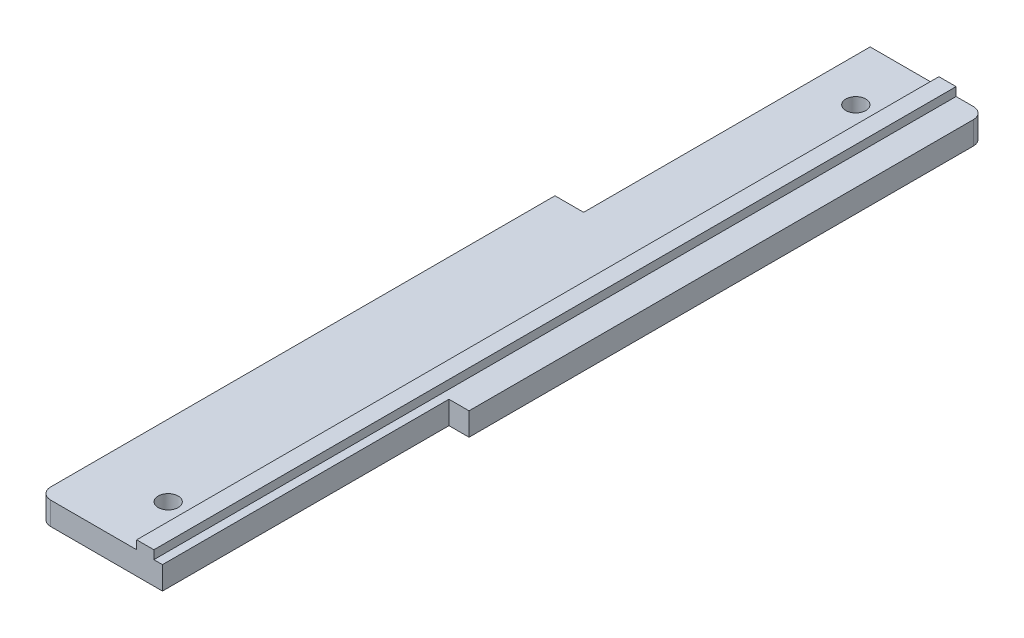
SolidWorks part; units mm, degrees
ref_plane "前视基准面" through (0, 0, 0) normal (0, 0, 1) x (1, 0, 0)
ref_plane "上视基准面" through (0, 0, 0) normal (0, 1, 0) x (1, 0, 0)
ref_plane "右视基准面" through (0, 0, 0) normal (1, 0, 0) x (0, 0, -1)
sketch "草图1" plane through (0, 0, 0) normal (0, 1, 0) x (1, 0, 0)
  line L1 (-12.5, -70) -> (12.5, -70)
  line L2 (-12.5, -70) -> (-12.5, 70)
  line L3 (-12.5, 70) -> (12.5, 70)
  line L4 (12.5, -70) -> (12.5, 70)
  line L5 (-12.5, -70) -> (12.5, 70) construction
  line L6 (-12.5, 70) -> (12.5, -70) construction
  point P0 (0, 0)
  dimension "D1" = 25
  dimension "D2" = 140
extrude "凸台-拉伸1" add sketch "草图1" along normal blind 4
sketch "草图2" plane through (0, 4, 0) normal (0, 1, 0) x (1, 0, 0)
  line L0 (0, 70) -> (0, -70) construction
  line L1 (12.5, 70) -> (-12.5, 70) construction
  line L2 (-12.5, -70) -> (12.5, -70) construction
  line L3 (0, 0) -> (12.5, 0) construction
  line L4 (12.5, -70) -> (12.5, 70) construction
  circle A0 centre (0, 0) radius 1.6 construction
  circle A1 centre (0, 20) radius 1.6 construction
  circle A2 centre (0, 40) radius 1.6 construction
  circle A3 centre (0, -40) radius 1.6 construction
  circle A4 centre (0, -20) radius 1.6 construction
  circle A5 centre (0, 10) radius 1.6
  circle A6 centre (0, 30) radius 1.6
  circle A7 centre (0, 50) radius 1.6
  circle A8 centre (0, -10) radius 1.6
  circle A9 centre (0, -30) radius 1.6
  circle A10 centre (0, -50) radius 1.6
  dimension "D1" = 3.2
  dimension "D4" = 3.2
  dimension "D3" = 20
  dimension "D5" = 10
  dimension "D7" = 20
  dimension "D2" = 3
  dimension "D6" = 3
sketch "草图3" plane through (0, 4, 0) normal (0, 1, 0) x (1, 0, 0)
  line L0 (-12.5, 0) -> (12.5, 0) construction
  line L1 (-12.5, 70) -> (-12.5, -70) construction
  line L2 (12.5, -70) -> (12.5, 70) construction
  line L3 (-12.5, 30) -> (12.5, 30) construction
  line L4 (0, 0) -> (0, 30) construction
  line B0 (-8, 37.5) -> (-8, 22.5) construction
  line B1 (-8, 37.5) -> (8, 37.5) construction
  line B2 (8, 37.5) -> (8, 22.5) construction
  line B3 (-8, 22.5) -> (8, 22.5) construction
  line B4 (0, 37.5) -> (0, 30) construction
  circle B5 centre (8, 37.5) radius 1.6
  circle B6 centre (8, 22.5) radius 1.6
  circle B7 centre (-8, 37.5) radius 1.6
  circle B8 centre (-8, 22.5) radius 1.6
  line B9 (-8, -37.5) -> (-8, -22.5) construction
  line B10 (-8, -37.5) -> (8, -37.5) construction
  line B11 (8, -37.5) -> (8, -22.5) construction
  line B12 (-8, -22.5) -> (8, -22.5) construction
  circle B13 centre (8, -37.5) radius 1.6
  circle B14 centre (8, -22.5) radius 1.6
  circle B15 centre (-8, -37.5) radius 1.6
  circle B16 centre (-8, -22.5) radius 1.6
  dimension "D1" = 30
sketch_block_instance "MGN9H导轨滑块孔-1"
sketch_block "MGN9H导轨滑块孔" parameters "D3"=3.2, "D1"=15, "D2"=16
sketch_block_instance "MGN9H导轨滑块孔-3"
fillet "圆角1" radius 2 4 edges at (12.5, 2, -70) (-12.5, 2, -70) (-12.5, 2, 70) (12.5, 2, 70)
sketch "草图4" plane through (0, 4, 0) normal (0, 1, 0) x (1, 0, 0)
  line L0 (-12.5, 0) -> (0, 0) construction
  line L1 (-12.5, 68) -> (-12.5, -68) construction
  line L2 (0, 70) -> (0, -70) construction
  circle A0 centre (0, 60) radius 1.75
  circle A1 centre (0, -60) radius 1.75
  dimension "D1" = 3.5
  dimension "D2" = 120
extrude "切除-拉伸1" cut sketch "草图4" against normal blind 10
sketch "草图6" plane through (0, 4, 0) normal (0, 1, 0) x (1, 0, 0)
  line L0 (10.5, 70) -> (-10.5, 70) construction
  line L1 (4.5, 70) -> (7.5, 70)
  line L2 (4.5, 70) -> (4.5, -70)
  line L3 (4.5, -70) -> (7.5, -70)
  line L4 (7.5, 70) -> (7.5, -70)
  line L5 (-10.5, -70) -> (10.5, -70) construction
  line L6 (12.5, -68) -> (12.5, 68) construction
  dimension "D1" = 8
  dimension "D2" = 3
extrude "凸台-拉伸3" add sketch "草图6" along normal blind 1.5
sketch "草图7" plane through (0, 4, 0) normal (0, 1, 0) x (1, 0, 0)
  line L0 (4.5, 70) -> (-10.5, 70) construction
  line L1 (-7.5, 70) -> (-28.1119, 70)
  line L2 (-7.5, 70) -> (-7.5, 20)
  line L3 (-7.5, 20) -> (-28.1119, 20)
  line L4 (-28.1119, 70) -> (-28.1119, 20)
  line L5 (-12.5, 68) -> (-12.5, -68) construction
  dimension "D1" = 5
  dimension "D2" = 50
extrude "切除-拉伸2" cut sketch "草图7" against normal blind 10
sketch "草图8" plane through (0, 4, 0) normal (0, 1, 0) x (1, 0, 0)
  line L0 (12.5, -68) -> (12.5, 68) construction
  line L1 (12.5, -20) -> (9, -20)
  line L2 (12.5, -20) -> (12.5, -70)
  line L3 (12.5, -70) -> (9, -70)
  line L4 (9, -20) -> (9, -70)
  line L5 (7.5, -70) -> (10.5, -70) construction
  dimension "D1" = 50
extrude "切除-拉伸3" cut sketch "草图8" against normal blind 45
